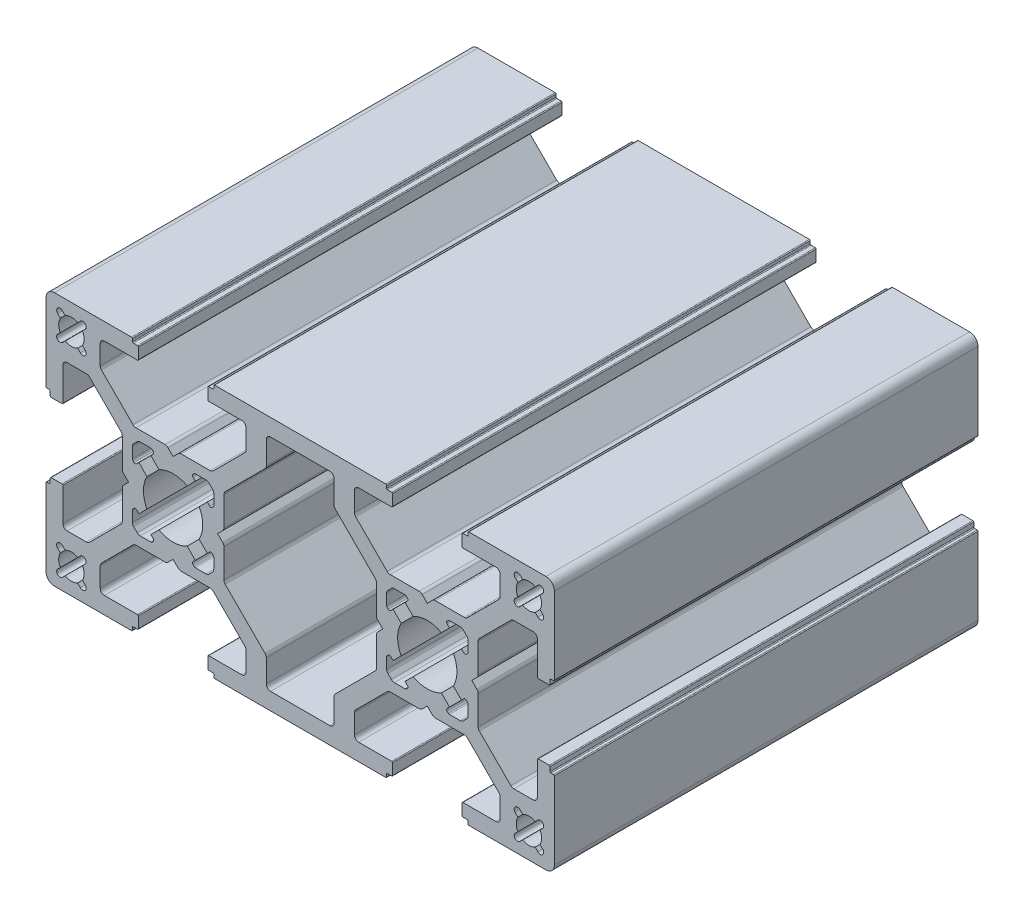
SolidWorks part; units mm, degrees
material "6061 Alaşım"
ref_plane "Ön Düzlem" through (0, 0, 0) normal (0, 0, 1) x (1, 0, 0)
ref_plane "Üst Düzlem" through (0, 0, 0) normal (0, 1, 0) x (1, 0, 0)
ref_plane "Sağ Düzlem" through (0, 0, 0) normal (1, 0, 0) x (0, 0, -1)
sketch "Çizim1" plane through (0, 0, 0) normal (0, 0, 1) x (1, 0, 0)
  line L0 (-4.8, 14.9) -> (-4.8, 14.6)
  line L1 (15, -15) -> (-15, -15) construction
  line L2 (15, -15) -> (15, 15) construction
  line L3 (15, 15) -> (-15, 15) construction
  line L4 (-15, -15) -> (-15, 15) construction
  line L5 (0, 15) -> (0, -15) construction
  line L6 (15, 0) -> (-15, 0) construction
  line L7 (-4.7, 14.5) -> (-4.2, 14.5)
  line L8 (-4.1, 14.4) -> (-4.1, 13.1)
  line L9 (-4.2, 13) -> (-8.1, 13)
  line L10 (-8.6, 12.5) -> (-8.6, 10.2213)
  line L11 (-8.4536, 9.8678) -> (-4.7322, 6.1464)
  line L12 (-4.3787, 6) -> (-0.9571, 6)
  line L13 (-0.6036, 5.8536) -> (0, 5.25)
  line L14 (-15, 15) -> (0, 0) construction
  line L15 (-4.9, 15) -> (-14, 15)
  line L16 (-4.5858, 6) -> (-1.6646, 3.0788) construction
  line L17 (-4.6536, 4.2393) -> (-4.2393, 4.6536)
  line L18 (-3.8858, 4.8) -> (-2.6201, 4.8)
  line L19 (-2.4787, 4.7414) -> (-2.3414, 4.6042)
  line L20 (-2.3414, 4.3213) -> (-2.6243, 4.0385)
  line L21 (-2.6243, 4.0385) -> (-1.6646, 3.0788)
  line L22 (0, 5.25) -> (0, 3.5)
  line L23 (-13.0607, 10.9393) -> (-10.9393, 13.0607) construction
  line L24 (-10.9393, 13.0607) -> (-10.6565, 13.3435) construction
  line L25 (-11.2606, 13.3051) -> (-10.9393, 13.6263)
  line L26 (-10.6949, 12.7394) -> (-10.3737, 13.0607)
  line L27 (-10.3737, 10.9393) -> (-10.6949, 11.2606)
  line L28 (-10.9393, 13.6263) -> (-10.3737, 13.0607) construction
  line L29 (-10.6565, 10.6565) -> (-10.3737, 10.9393) construction
  line L31 (-10.3737, 10.3737) -> (-4.4464, 4.4464) construction
  line L32 (-10.9393, 10.3737) -> (-11.2606, 10.6949)
  line L33 (-12.7394, 10.6949) -> (-13.0607, 10.3737)
  line L34 (-13.3051, 11.2606) -> (-13.6263, 10.9393)
  line L35 (-15, 4.9) -> (-15, 14)
  line L36 (-14.9, 4.8) -> (-14.6, 4.8)
  line L37 (-14.5, 4.7) -> (-14.5, 4.2)
  line L38 (-14.4, 4.1) -> (-13.1, 4.1)
  line L39 (-13, 4.2) -> (-13, 8.1)
  line L40 (-12.5, 8.6) -> (-10.2213, 8.6)
  line L41 (-9.8678, 8.4536) -> (-6.1464, 4.7322)
  line L42 (-6, 4.3787) -> (-6, 0.9571)
  line L43 (-5.8536, 0.6036) -> (-5.25, 0)
  line L44 (-5.25, 0) -> (-3.5, 0)
  line L45 (-4.0385, 2.6243) -> (-3.0788, 1.6646)
  line L46 (-4.3213, 2.3414) -> (-4.0385, 2.6243)
  line L47 (-4.7414, 2.4787) -> (-4.6042, 2.3414)
  line L48 (-4.8, 3.8858) -> (-4.8, 2.6201)
  line L49 (-13.0607, 13.6263) -> (-12.7394, 13.3051)
  line L50 (-13.6263, 13.0607) -> (-13.3051, 12.7394)
  line L57 (9.8678, 8.4536) -> (6.1464, 4.7322)
  line L58 (6, 4.3787) -> (6, 0.9571)
  line L59 (5.8536, 0.6036) -> (5.25, 0)
  line L60 (5.25, 0) -> (3.5, 0)
  line L61 (4.0385, 2.6243) -> (3.0788, 1.6646)
  line L62 (4.3213, 2.3414) -> (4.0385, 2.6243)
  line L63 (4.7414, 2.4787) -> (4.6042, 2.3414)
  line L64 (4.8, 3.8858) -> (4.8, 2.6201)
  line L65 (4.2393, 4.6536) -> (4.6536, 4.2393)
  line L66 (3.8858, 4.8) -> (2.6201, 4.8)
  line L67 (2.4787, 4.7414) -> (2.3414, 4.6042)
  line L68 (2.3414, 4.3213) -> (2.6243, 4.0385)
  line L69 (2.6243, 4.0385) -> (1.6646, 3.0788)
  line L70 (0, 5.25) -> (0, 3.5)
  line L71 (0.6036, 5.8536) -> (0, 5.25)
  line L72 (4.3787, 6) -> (0.9571, 6)
  line L73 (8.4536, 9.8678) -> (4.7322, 6.1464)
  line L74 (8.6, 12.5) -> (8.6, 10.2213)
  line L75 (4.2, 13) -> (8.1, 13)
  line L76 (4.1, 14.4) -> (4.1, 13.1)
  line L77 (4.7, 14.5) -> (4.2, 14.5)
  line L78 (4.8, 14.9) -> (4.8, 14.6)
  line L79 (4.9, 15) -> (14, 15)
  line L125 (-15, -4.9) -> (-15, -14)
  line L126 (-14.9, -4.8) -> (-14.6, -4.8)
  line L127 (-14.5, -4.7) -> (-14.5, -4.2)
  line L128 (-14.4, -4.1) -> (-13.1, -4.1)
  line L129 (-13, -4.2) -> (-13, -8.1)
  line L130 (-12.5, -8.6) -> (-10.2213, -8.6)
  line L131 (-9.8678, -8.4536) -> (-6.1464, -4.7322)
  line L132 (-6, -4.3787) -> (-6, -0.9571)
  line L133 (-5.8536, -0.6036) -> (-5.25, 0)
  line L134 (-5.25, 0) -> (-3.5, 0)
  line L135 (-4.0385, -2.6243) -> (-3.0788, -1.6646)
  line L136 (-4.3213, -2.3414) -> (-4.0385, -2.6243)
  line L137 (-4.7414, -2.4787) -> (-4.6042, -2.3414)
  line L138 (-4.8, -3.8858) -> (-4.8, -2.6201)
  line L139 (-4.2393, -4.6536) -> (-4.6536, -4.2393)
  line L140 (-3.8858, -4.8) -> (-2.6201, -4.8)
  line L141 (-2.4787, -4.7414) -> (-2.3414, -4.6042)
  line L142 (-2.3414, -4.3213) -> (-2.6243, -4.0385)
  line L143 (-2.6243, -4.0385) -> (-1.6646, -3.0788)
  line L144 (0, -5.25) -> (0, -3.5)
  line L145 (-0.6036, -5.8536) -> (0, -5.25)
  line L146 (-4.3787, -6) -> (-0.9571, -6)
  line L147 (-8.4536, -9.8678) -> (-4.7322, -6.1464)
  line L148 (-8.6, -12.5) -> (-8.6, -10.2213)
  line L149 (-4.2, -13) -> (-8.1, -13)
  line L150 (-4.1, -14.4) -> (-4.1, -13.1)
  line L151 (-4.7, -14.5) -> (-4.2, -14.5)
  line L152 (-4.8, -14.9) -> (-4.8, -14.6)
  line L153 (-4.9, -15) -> (-14, -15)
  line L154 (-13.3051, -11.2606) -> (-13.6263, -10.9393)
  line L155 (-12.7394, -10.6949) -> (-13.0607, -10.3737)
  line L156 (-10.9393, -10.3737) -> (-11.2606, -10.6949)
  line L157 (-10.3737, -10.9393) -> (-10.6949, -11.2606)
  line L158 (-10.6949, -12.7394) -> (-10.3737, -13.0607)
  line L159 (-11.2606, -13.3051) -> (-10.9393, -13.6263)
  line L160 (-13.0607, -13.6263) -> (-12.7394, -13.3051)
  line L161 (-13.6263, -13.0607) -> (-13.3051, -12.7394)
  line L162 (-15, 14) -> (-15, 15)
  line L163 (-15, 15) -> (-14, 15)
  line L164 (-15, -14) -> (-15, -15)
  line L165 (-15, -15) -> (-14, -15)
  line L166 (11, 12.5) -> (11, 9.7929)
  line L189 (10.8536, 9.4393) -> (9.8678, 8.4536)
  line L190 (11.5, 13) -> (15, 13)
  line L191 (14, 15) -> (15, 15)
  line L192 (15, 15) -> (15, 13)
  line L222 (16.5, 0) -> (-16.5, 0) construction
  line L223 (14, -15) -> (15, -15)
  line L224 (4.9, -15) -> (14, -15)
  line L225 (4.8, -14.9) -> (4.8, -14.6)
  line L226 (4.7, -14.5) -> (4.2, -14.5)
  line L227 (4.1, -14.4) -> (4.1, -13.1)
  line L228 (4.2, -13) -> (8.1, -13)
  line L229 (8.6, -12.5) -> (8.6, -10.2213)
  line L230 (8.4536, -9.8678) -> (4.7322, -6.1464)
  line L231 (4.3787, -6) -> (0.9571, -6)
  line L232 (0.6036, -5.8536) -> (0, -5.25)
  line L233 (0, -5.25) -> (0, -3.5)
  line L234 (2.6243, -4.0385) -> (1.6646, -3.0788)
  line L235 (2.3414, -4.3213) -> (2.6243, -4.0385)
  line L236 (2.4787, -4.7414) -> (2.3414, -4.6042)
  line L237 (3.8858, -4.8) -> (2.6201, -4.8)
  line L238 (4.2393, -4.6536) -> (4.6536, -4.2393)
  line L239 (4.8, -3.8858) -> (4.8, -2.6201)
  line L240 (4.7414, -2.4787) -> (4.6042, -2.3414)
  line L241 (4.3213, -2.3414) -> (4.0385, -2.6243)
  line L242 (4.0385, -2.6243) -> (3.0788, -1.6646)
  line L243 (5.8536, -0.6036) -> (5.25, 0)
  line L244 (6, -4.3787) -> (6, -0.9571)
  line L245 (9.8678, -8.4536) -> (6.1464, -4.7322)
  line L246 (10.8536, -9.4393) -> (9.8678, -8.4536)
  line L247 (11, -12.5) -> (11, -9.7929)
  line L248 (11.5, -13) -> (15, -13)
  line L249 (15, -15) -> (15, -13)
  circle A0 centre (-12, 12) radius 1.5 construction
  circle A1 centre (0, 0) radius 3.5 construction
  arc A2 (-1.6646, 3.0788) -> (0, 3.5) centre (0, 0) cw
  circle A3 centre (-10.6565, 10.6565) radius 0.4 construction
  circle A4 centre (-10.6565, 13.3435) radius 0.4 construction
  arc A5 (-10.9393, 13.6263) -> (-10.3737, 13.0607) centre (-10.6565, 13.3435) cw
  arc A6 (-13.3051, 11.2606) -> (-13.3051, 12.7394) centre (-12, 12) cw
  arc A7 (-10.6949, 12.7394) -> (-10.6949, 11.2606) centre (-12, 12) cw
  arc A8 (-10.3737, 10.9393) -> (-10.9393, 10.3737) centre (-10.6565, 10.6565) cw
  arc A9 (-4.1, 13.1) -> (-4.2, 13) centre (-4.2, 13.1) cw
  arc A10 (-4.2, 14.5) -> (-4.1, 14.4) centre (-4.2, 14.4) cw
  arc A11 (-4.8, 14.6) -> (-4.7, 14.5) centre (-4.7, 14.6) ccw
  arc A12 (-4.8, 14.9) -> (-4.9, 15) centre (-4.9, 14.9) ccw
  arc A13 (-4.2393, 4.6536) -> (-3.8858, 4.8) centre (-3.8858, 4.3) cw
  arc A14 (-0.9571, 6) -> (-0.6036, 5.8536) centre (-0.9571, 5.5) cw
  arc A15 (-4.7322, 6.1464) -> (-4.3787, 6) centre (-4.3787, 6.5) ccw
  arc A16 (-8.6, 10.2213) -> (-8.4536, 9.8678) centre (-8.1, 10.2213) ccw
  arc A17 (-8.1, 13) -> (-8.6, 12.5) centre (-8.1, 12.5) ccw
  arc A18 (-2.3414, 4.6042) -> (-2.3414, 4.3213) centre (-2.4828, 4.4627) cw
  arc A19 (-2.6201, 4.8) -> (-2.4787, 4.7414) centre (-2.6201, 4.6) cw
  arc A20 (-12.7394, 10.6949) -> (-11.2606, 10.6949) centre (-12, 12) ccw
  arc A21 (-13.6263, 10.9393) -> (-13.0607, 10.3737) centre (-13.3435, 10.6565) ccw
  arc A22 (-14.9, 4.8) -> (-15, 4.9) centre (-14.9, 4.9) cw
  arc A23 (-14.6, 4.8) -> (-14.5, 4.7) centre (-14.6, 4.7) cw
  arc A24 (-14.5, 4.2) -> (-14.4, 4.1) centre (-14.4, 4.2) ccw
  arc A25 (-13.1, 4.1) -> (-13, 4.2) centre (-13.1, 4.2) ccw
  arc A26 (-13, 8.1) -> (-12.5, 8.6) centre (-12.5, 8.1) cw
  arc A27 (-10.2213, 8.6) -> (-9.8678, 8.4536) centre (-10.2213, 8.1) cw
  arc A28 (-6.1464, 4.7322) -> (-6, 4.3787) centre (-6.5, 4.3787) cw
  arc A29 (-6, 0.9571) -> (-5.8536, 0.6036) centre (-5.5, 0.9571) ccw
  arc A30 (-3.0788, 1.6646) -> (-3.5, 0) centre (0, 0) ccw
  arc A31 (-4.6042, 2.3414) -> (-4.3213, 2.3414) centre (-4.4627, 2.4828) ccw
  arc A32 (-4.8, 2.6201) -> (-4.7414, 2.4787) centre (-4.6, 2.6201) ccw
  arc A33 (-4.6536, 4.2393) -> (-4.8, 3.8858) centre (-4.3, 3.8858) ccw
  arc A34 (-15, 14) -> (-14, 15) centre (-14, 14) cw
  arc A35 (-13.0607, 13.6263) -> (-13.6263, 13.0607) centre (-13.3435, 13.3435) ccw
  arc A36 (-12.7394, 13.3051) -> (-11.2606, 13.3051) centre (-12, 12) cw
  arc A45 (6.1464, 4.7322) -> (6, 4.3787) centre (6.5, 4.3787) ccw
  arc A46 (6, 0.9571) -> (5.8536, 0.6036) centre (5.5, 0.9571) cw
  arc A47 (3.0788, 1.6646) -> (3.0788, -1.6646) centre (0, 0) cw
  arc A48 (4.6042, 2.3414) -> (4.3213, 2.3414) centre (4.4627, 2.4828) cw
  arc A49 (4.8, 2.6201) -> (4.7414, 2.4787) centre (4.6, 2.6201) cw
  arc A50 (4.6536, 4.2393) -> (4.8, 3.8858) centre (4.3, 3.8858) cw
  arc A51 (4.2393, 4.6536) -> (3.8858, 4.8) centre (3.8858, 4.3) ccw
  arc A52 (2.6201, 4.8) -> (2.4787, 4.7414) centre (2.6201, 4.6) ccw
  arc A53 (2.3414, 4.6042) -> (2.3414, 4.3213) centre (2.4828, 4.4627) ccw
  arc A54 (1.6646, 3.0788) -> (0, 3.5) centre (0, 0) ccw
  arc A55 (0.9571, 6) -> (0.6036, 5.8536) centre (0.9571, 5.5) ccw
  arc A56 (4.7322, 6.1464) -> (4.3787, 6) centre (4.3787, 6.5) cw
  arc A57 (8.6, 10.2213) -> (8.4536, 9.8678) centre (8.1, 10.2213) cw
  arc A58 (8.1, 13) -> (8.6, 12.5) centre (8.1, 12.5) cw
  arc A59 (4.1, 13.1) -> (4.2, 13) centre (4.2, 13.1) ccw
  arc A60 (4.2, 14.5) -> (4.1, 14.4) centre (4.2, 14.4) ccw
  arc A61 (4.8, 14.6) -> (4.7, 14.5) centre (4.7, 14.6) cw
  arc A62 (4.8, 14.9) -> (4.9, 15) centre (4.9, 14.9) cw
  arc A103 (-13.3051, -12.7394) -> (-13.3051, -11.2606) centre (-12, -12) cw
  arc A104 (-14, -15) -> (-15, -14) centre (-14, -14) cw
  arc A105 (-14.9, -4.8) -> (-15, -4.9) centre (-14.9, -4.9) ccw
  arc A106 (-14.6, -4.8) -> (-14.5, -4.7) centre (-14.6, -4.7) ccw
  arc A107 (-14.5, -4.2) -> (-14.4, -4.1) centre (-14.4, -4.2) cw
  arc A108 (-13.1, -4.1) -> (-13, -4.2) centre (-13.1, -4.2) cw
  arc A109 (-13, -8.1) -> (-12.5, -8.6) centre (-12.5, -8.1) ccw
  arc A110 (-10.2213, -8.6) -> (-9.8678, -8.4536) centre (-10.2213, -8.1) ccw
  arc A111 (-6.1464, -4.7322) -> (-6, -4.3787) centre (-6.5, -4.3787) ccw
  arc A112 (-6, -0.9571) -> (-5.8536, -0.6036) centre (-5.5, -0.9571) cw
  arc A113 (-3.0788, -1.6646) -> (-3.5, 0) centre (0, 0) cw
  arc A114 (-4.6042, -2.3414) -> (-4.3213, -2.3414) centre (-4.4627, -2.4828) cw
  arc A115 (-4.8, -2.6201) -> (-4.7414, -2.4787) centre (-4.6, -2.6201) cw
  arc A116 (-4.6536, -4.2393) -> (-4.8, -3.8858) centre (-4.3, -3.8858) cw
  arc A117 (-4.2393, -4.6536) -> (-3.8858, -4.8) centre (-3.8858, -4.3) ccw
  arc A118 (-2.6201, -4.8) -> (-2.4787, -4.7414) centre (-2.6201, -4.6) ccw
  arc A119 (-2.3414, -4.6042) -> (-2.3414, -4.3213) centre (-2.4828, -4.4627) ccw
  arc A120 (-1.6646, -3.0788) -> (0, -3.5) centre (0, 0) ccw
  arc A121 (-0.9571, -6) -> (-0.6036, -5.8536) centre (-0.9571, -5.5) ccw
  arc A122 (-4.7322, -6.1464) -> (-4.3787, -6) centre (-4.3787, -6.5) cw
  arc A123 (-8.6, -10.2213) -> (-8.4536, -9.8678) centre (-8.1, -10.2213) cw
  arc A124 (-8.1, -13) -> (-8.6, -12.5) centre (-8.1, -12.5) cw
  arc A125 (-4.1, -13.1) -> (-4.2, -13) centre (-4.2, -13.1) ccw
  arc A126 (-4.2, -14.5) -> (-4.1, -14.4) centre (-4.2, -14.4) ccw
  arc A127 (-4.8, -14.6) -> (-4.7, -14.5) centre (-4.7, -14.6) cw
  arc A128 (-4.8, -14.9) -> (-4.9, -15) centre (-4.9, -14.9) cw
  arc A129 (-13.6263, -10.9393) -> (-13.0607, -10.3737) centre (-13.3435, -10.6565) cw
  arc A130 (-12.7394, -10.6949) -> (-11.2606, -10.6949) centre (-12, -12) cw
  arc A131 (-10.9393, -10.3737) -> (-10.3737, -10.9393) centre (-10.6565, -10.6565) cw
  arc A132 (-10.6949, -12.7394) -> (-10.6949, -11.2606) centre (-12, -12) ccw
  arc A133 (-10.9393, -13.6263) -> (-10.3737, -13.0607) centre (-10.6565, -13.3435) ccw
  arc A134 (-11.2606, -13.3051) -> (-12.7394, -13.3051) centre (-12, -12) cw
  arc A135 (-13.6263, -13.0607) -> (-13.0607, -13.6263) centre (-13.3435, -13.3435) ccw
  arc A184 (11, 12.5) -> (11.5, 13) centre (11.5, 12.5) cw
  arc A185 (11, 9.7929) -> (10.8536, 9.4393) centre (10.5, 9.7929) cw
  arc A186 (4.8, -14.9) -> (4.9, -15) centre (4.9, -14.9) ccw
  arc A187 (4.8, -14.6) -> (4.7, -14.5) centre (4.7, -14.6) ccw
  arc A188 (4.2, -14.5) -> (4.1, -14.4) centre (4.2, -14.4) cw
  arc A189 (4.1, -13.1) -> (4.2, -13) centre (4.2, -13.1) cw
  arc A190 (8.1, -13) -> (8.6, -12.5) centre (8.1, -12.5) ccw
  arc A191 (8.6, -10.2213) -> (8.4536, -9.8678) centre (8.1, -10.2213) ccw
  arc A192 (4.7322, -6.1464) -> (4.3787, -6) centre (4.3787, -6.5) ccw
  arc A193 (0.9571, -6) -> (0.6036, -5.8536) centre (0.9571, -5.5) cw
  arc A194 (1.6646, -3.0788) -> (0, -3.5) centre (0, 0) cw
  arc A195 (2.3414, -4.6042) -> (2.3414, -4.3213) centre (2.4828, -4.4627) cw
  arc A196 (2.6201, -4.8) -> (2.4787, -4.7414) centre (2.6201, -4.6) cw
  arc A197 (4.2393, -4.6536) -> (3.8858, -4.8) centre (3.8858, -4.3) cw
  arc A198 (4.6536, -4.2393) -> (4.8, -3.8858) centre (4.3, -3.8858) ccw
  arc A199 (4.8, -2.6201) -> (4.7414, -2.4787) centre (4.6, -2.6201) ccw
  arc A200 (4.6042, -2.3414) -> (4.3213, -2.3414) centre (4.4627, -2.4828) ccw
  arc A201 (6, -0.9571) -> (5.8536, -0.6036) centre (5.5, -0.9571) ccw
  arc A202 (6.1464, -4.7322) -> (6, -4.3787) centre (6.5, -4.3787) cw
  arc A203 (11, -9.7929) -> (10.8536, -9.4393) centre (10.5, -9.7929) ccw
  arc A204 (11, -12.5) -> (11.5, -13) centre (11.5, -12.5) ccw
  point P0 (0, 0)
  point P27 (-12, 12)
  point P38 (-10.6565, 13.3435)
  point P49 (-4.1, 14.5)
  point P52 (-4.8, 14.5)
  point P55 (-4.8, 15)
  point P58 (-4.0929, 4.8)
  point P61 (-0.75, 6)
  point P71 (-2.2, 4.4627)
  point P435 (0, 0)
  dimension "D8" = 3
  dimension "D13" = 7
  dimension "D18" = 0.8
  dimension "D19" = 0.8
  dimension "D20" = 0.1
  dimension "D21" = 0.5
  dimension "D22" = 0.2
  dimension "D23" = 1
  dimension "D27" = 0.5
  dimension "D1" = 30
  dimension "D2" = 30
  dimension "D3" = 2
  dimension "D4" = 0.5
  dimension "D5" = 0.7
  dimension "D6" = 8.2
  dimension "D7" = 2
  dimension "D9" = 6
  dimension "D10" = 0.75
  dimension "D11" = 4.5
  dimension "D12" = 3
  dimension "D14" = 0.6
  dimension "D15" = 0.5
  dimension "D16" = 1.2
  dimension "D17" = 2.2
  dimension "D25" = 2
  dimension "D26" = 4
extrude "Yükseklik-Ekstrüzyon1" add sketch "Çizim1" against normal blind 50 contours A34 L35 A22 L36 A23 L37 A24 L38 A25 L39 A26 L40 A27 L41 A28 L42 A29 L43 L44 A30 L45 L46 A31 L47 A32 L48 A33 L17 A13 L18 A19 L19 A18 L20 L21 A2 L22 L13 A14 L12 A15 L11 A16 L10 A17 L9 A9 L8 A10 L7 A11 | A128 L152 A127 L151 A126 L150 A125 L149 A124 L148 A123 L147 A122 L146 A121 L145 L144 A120 L143 L142 A119 L141 A118 L140 A117 L139 A116 L138 A115 L137 A114 L136 L135 A113 L44 L133 A112 L132 A111 L131 A110 L130 A109 L129 A108 L128 A107 L127 A106 L126 A105 | A185 L166 A184 L190 L192 L191 L79 A62 L78 A61 L77 A60 L76 A59 L75 A58 L74 A57 L73 A56 L72 A55 L71 L22 A54 L69 L68 A53 L67 A52 L66 A51 L65 A50 L64 A49 L63 A48 L62 L61 A47 L60 L59 A46 L58 A45 L57 L189 | A204 L247 A203 L246 L245 A202 L244 A201 L243 L60 A47 L242 L241 A200 L240 A199 L239 A198 L238 A197 L237 A196 L236 A195 L235 L234 A194 L144 L232 A193 L231 A192 L230 A191 L229 A190 L228 A189 L227 A188 L226 A187 L225 A186 L224 L223 L249 L248
mirror "Aynalama1" about plane through (15, 0, -50) normal (1, 0, 0) of bodies 102
